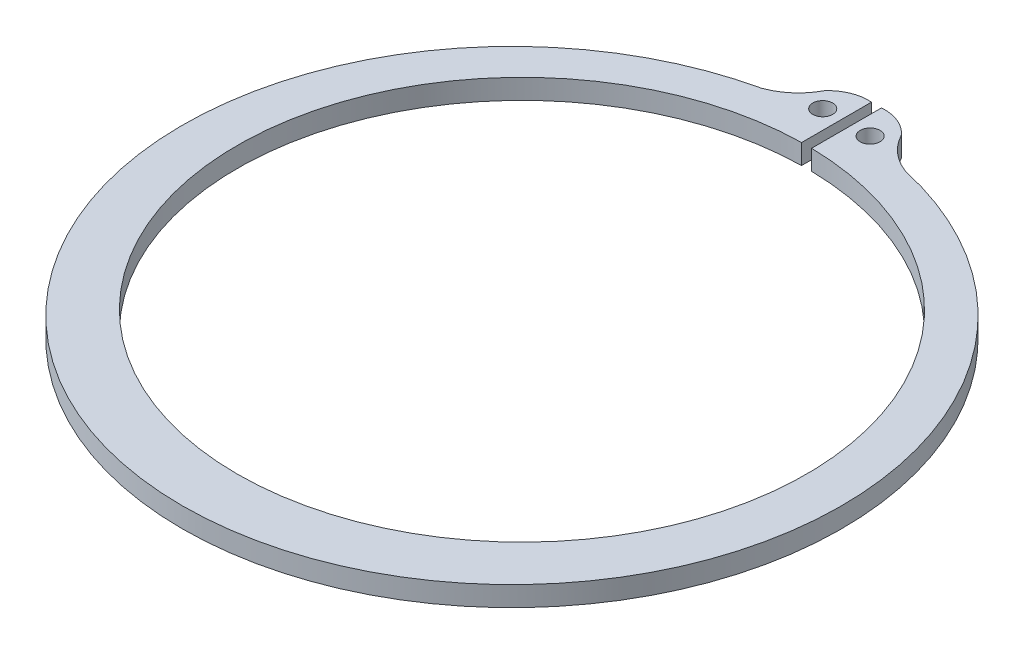
SolidWorks part; units mm, degrees
ref_plane "Plano frontal" through (0, 0, 0) normal (0, 0, 1) x (1, 0, 0)
ref_plane "Plano superior" through (0, 0, 0) normal (0, 1, 0) x (1, 0, 0)
ref_plane "Plano direito" through (0, 0, 0) normal (1, 0, 0) x (0, 0, -1)
sketch "Esboço1" plane through (0, 0, 0) normal (0, 1, 0) x (1, 0, 0)
  line L3 (0, -1) -> (0, 44.4403) construction
  line L4 (-0.5, 35.4956) -> (-0.5, 28.4956)
  line L5 (0.5, 35.4956) -> (0.5, 28.4956)
  arc A1 (-0.5, 28.4956) -> (0.5, 28.4956) centre (0, 0) ccw
  arc A2 (-0.5, 35.4956) -> (-3.8486, 34.1308) centre (-0.8127, 31.4725) ccw
  arc A3 (-3.8486, 34.1308) -> (-7.1686, 31.212) centre (-9.3481, 37.0387) cw
  arc A4 (3.8486, 34.1308) -> (7.1686, 31.212) centre (9.3481, 37.0387) ccw
  arc A5 (0.5, 35.4956) -> (3.8486, 34.1308) centre (0.8127, 31.4725) cw
  arc A6 (-7.1686, 31.212) -> (7.1686, 31.212) centre (0, -1) ccw
extrude "Ressalto-extrusão1" add sketch "Esboço1" along normal blind 2
sketch "Esboço2" plane through (0, 2, 0) normal (0, 1, 0) x (1, 0, 0)
  line L0 (0, 0) -> (0, -5.9097) construction
  circle A0 centre (-2.3731, 32.4842) radius 0.9956
  circle A1 centre (2.3731, 32.4842) radius 0.9956
extrude "Corte-extrusão1" cut sketch "Esboço2" against normal blind 2
